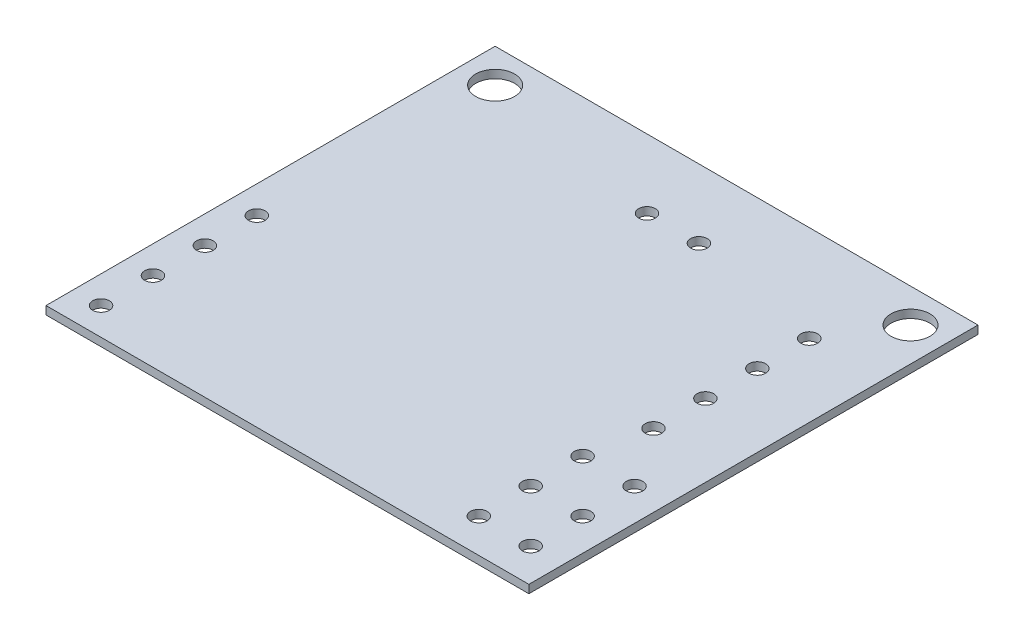
SolidWorks part; units mm, degrees
ref_plane "Front Plane" through (0, 0, 0) normal (0, 0, 1) x (1, 0, 0)
ref_plane "Top Plane" through (0, 0, 0) normal (0, 1, 0) x (1, 0, 0)
ref_plane "Right Plane" through (0, 0, 0) normal (1, 0, 0) x (0, 0, -1)
sketch "Sketch1" plane through (0, 0, 0) normal (0, 1, 0) x (1, 0, 0)
  line L1 (0, 0) -> (23.622, 0)
  line L2 (0, 0) -> (0, 21.971)
  line L3 (0, 21.971) -> (23.622, 21.971)
  line L4 (23.622, 0) -> (23.622, 21.971)
  circle A0 centre (1.651, 20.32) radius 0.9525
  circle A1 centre (21.971, 20.32) radius 0.9525
  circle A2 centre (13.335, 18.6055) radius 0.4064
  circle A3 centre (10.795, 18.6055) radius 0.4064
  circle A4 centre (1.3462, 8.9662) radius 0.4064
  circle A5 centre (1.3462, 6.4262) radius 0.4064
  circle A6 centre (1.3462, 3.8862) radius 0.4064
  circle A7 centre (1.3462, 1.3462) radius 0.4064
  circle A8 centre (22.0472, 1.6637) radius 0.4064
  circle A9 centre (19.5072, 1.6637) radius 0.4064
  circle A10 centre (19.5072, 4.2037) radius 0.4064
  circle A11 centre (19.5072, 6.7437) radius 0.4064
  circle A12 centre (22.0472, 4.2037) radius 0.4064
  circle A13 centre (22.0472, 6.7437) radius 0.4064
  circle A14 centre (20.066, 9.652) radius 0.4064
  circle A15 centre (20.066, 12.192) radius 0.4064
  circle A16 centre (20.066, 14.732) radius 0.4064
  circle A17 centre (20.066, 17.272) radius 0.4064
  point P9 (12.065, 18.6055)
  dimension "D3" = 1.27
  dimension "D5" = 0.8128
  dimension "D6" = 0.8128
  dimension "D7" = 4
  dimension "D8" = 2
  dimension "D10" = 4
  dimension "D1" = 23.622
  dimension "D2" = 21.971
  dimension "D4" = 1.27
  dimension "D9" = 3
extrude "Boss-Extrude1" add sketch "Sketch1" along normal blind 0.4
